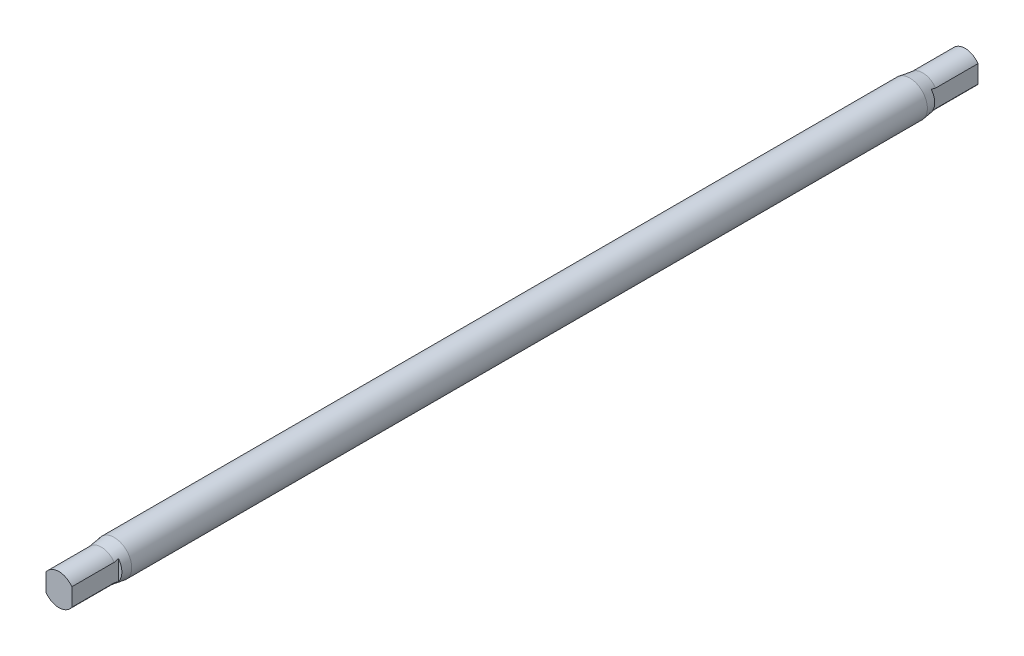
SolidWorks part; units mm, degrees
ref_plane "Front Plane" through (0, 0, 0) normal (0, 0, 1) x (1, 0, 0)
ref_plane "Top Plane" through (0, 0, 0) normal (0, 1, 0) x (1, 0, 0)
ref_plane "Right Plane" through (0, 0, 0) normal (1, 0, 0) x (0, 0, -1)
sketch "Sketch2" plane through (0, 0, 0) normal (1, 0, 0) x (0, 0, -1)
  line L0 (-215.9, 0) -> (215.9, 0) construction
  line L1 (-215.9, 9.525) -> (215.9, 9.525)
  line L2 (-215.9, 8.636) -> (215.9, 8.636)
  line L3 (215.9, 8.636) -> (215.9, 0)
  line L4 (215.9, 9.525) -> (222.9, 8.5)
  line L5 (222.9, 8.5) -> (245.9, 8.5)
  line L6 (245.9, 8.5) -> (245.9, 0)
  line L7 (245.9, 0) -> (215.9, 0)
  line L8 (0, 0) -> (0, 30.8008) construction
  line L9 (-245.9, 0) -> (-215.9, 0)
  line L10 (-245.9, 8.5) -> (-245.9, 0)
  line L11 (-222.9, 8.5) -> (-245.9, 8.5)
  line L12 (-215.9, 9.525) -> (-222.9, 8.5)
  line L13 (-215.9, 8.636) -> (-215.9, 0)
  point P4 (0, 0)
  dimension "D1" = 0.889
  dimension "D2" = 19.05
  dimension "D3" = 431.8
  dimension "D4" = 30
  dimension "D5" = 7
  dimension "D6" = 17
revolve "Revolve1" add sketch "Sketch2" angle 360 about L0
sketch3d "3DSketch1"
  line L0 (0, 0, -245.9) -> (0, 0, 245.9) construction
  line L1 (0, 0, 222.9) -> (0, 0, 245.9) construction
  point P6 (0, 0, 0)
sketch "Sketch3" plane through (0, 0, 0) normal (0, 1, 0) x (1, 0, 0)
  line L0 (-7, -220.562) -> (-26.7274, -220.562)
  line L1 (-26.7274, -220.562) -> (-26.7274, -252.5965)
  line L2 (-26.7274, -252.5965) -> (37.5225, -252.5965)
  line L3 (37.5225, -252.5965) -> (37.5225, -220.562)
  line L4 (37.5225, -220.562) -> (7, -220.562)
  line L5 (7, -220.562) -> (7, -245.9)
  line L6 (7, -245.9) -> (-7, -245.9)
  line L7 (-7, -245.9) -> (-7, -220.562)
  line L8 (0, 0) -> (0, -279.43) construction
  line L9 (0, 0) -> (75.4998, 0) construction
  line L10 (-7, 245.9) -> (-7, 220.562)
  line L11 (7, 245.9) -> (-7, 245.9)
  line L12 (7, 220.562) -> (7, 245.9)
  line L13 (37.5225, 220.562) -> (7, 220.562)
  line L14 (37.5225, 252.5965) -> (37.5225, 220.562)
  line L15 (-26.7274, 252.5965) -> (37.5225, 252.5965)
  line L16 (-26.7274, 220.562) -> (-26.7274, 252.5965)
  line L17 (-7, 220.562) -> (-26.7274, 220.562)
  line L20 (-8.5, -245.9) -> (8.5, -245.9) construction
  dimension "D1" = 14
  dimension "D2" = 25.338
  dimension "D3" = 32.0345
  dimension "D4" = 30.5225
  dimension "D5" = 19.7274
extrude "Cut-Extrude1" cut sketch "Sketch3" against normal through all both and the other way through all
